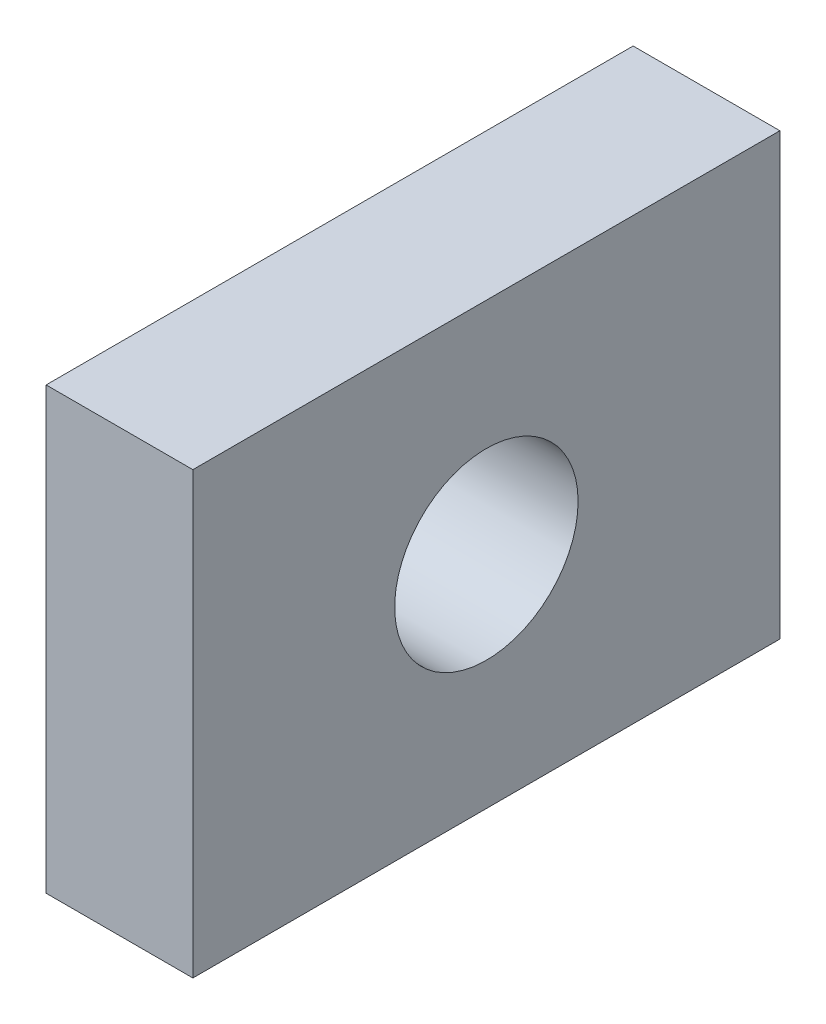
SolidWorks part; units mm, degrees
ref_plane "Front Plane" through (0, 0, 0) normal (0, 0, 1) x (1, 0, 0)
ref_plane "Top Plane" through (0, 0, 0) normal (0, 1, 0) x (1, 0, 0)
ref_plane "Right Plane" through (0, 0, 0) normal (1, 0, 0) x (0, 0, -1)
sketch "Sketch1" plane through (0, 0, 0) normal (1, 0, 0) x (0, 0, -1)
  line L0 (-50.8, 38.1) -> (50.8, -38.1) construction
  line L1 (-50.8, -38.1) -> (50.8, -38.1)
  line L2 (-50.8, -38.1) -> (-50.8, 38.1)
  line L3 (-50.8, 38.1) -> (50.8, 38.1)
  line L4 (50.8, -38.1) -> (50.8, 38.1)
  circle A0 centre (0, 0) radius 15.875
  point P7 (50.8, 7.0887)
  point P8 (-35.4101, -36.6433)
  dimension "D1" = 101.6
  dimension "D3" = 31.75
  dimension "D2" = 76.2
extrude "Boss-Extrude1" add sketch "Sketch1" along normal blind 25.4
